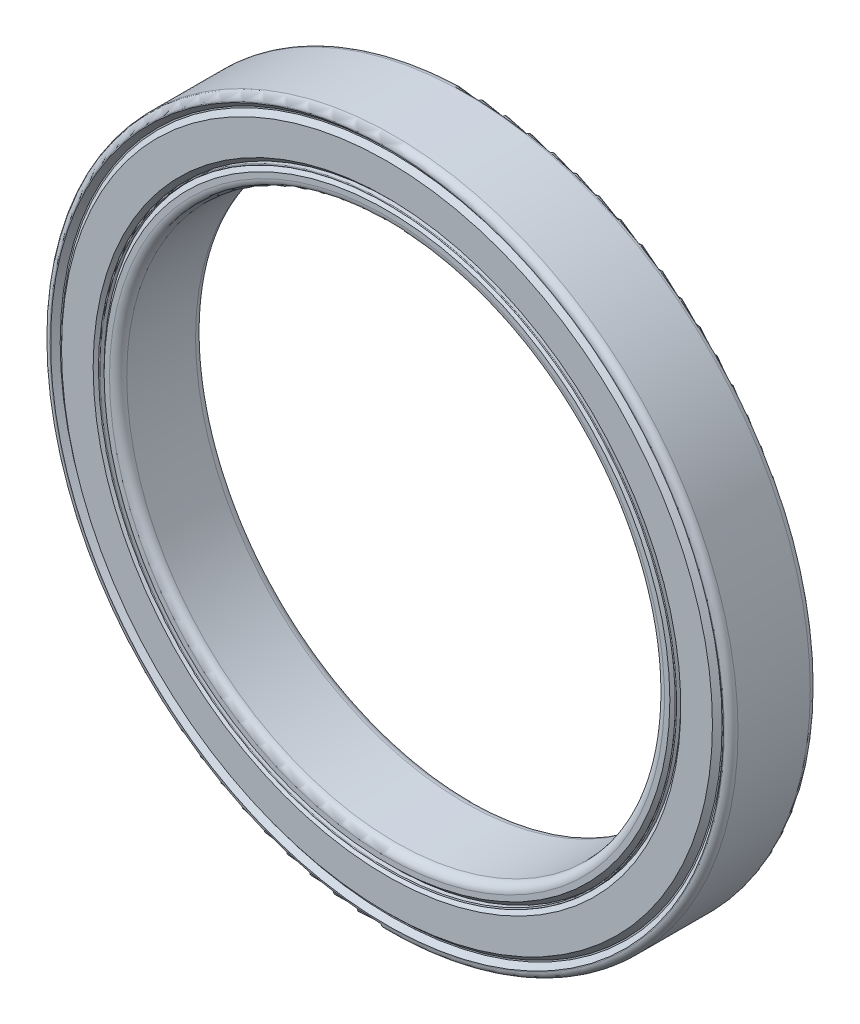
SolidWorks part; units mm, degrees
ref_plane "Front Plane" through (0, 0, 0) normal (0, 0, 1) x (1, 0, 0)
ref_plane "Top Plane" through (0, 0, 0) normal (0, 1, 0) x (1, 0, 0)
ref_plane "Right Plane" through (0, 0, 0) normal (1, 0, 0) x (0, 0, -1)
sketch "Sketch1" plane through (0, 0, 0) normal (0, 0, 1) x (1, 0, 0)
  line L0 (0, 14.25) -> (0, 16) construction
  line L1 (0, 12.5) -> (0, 14.25) construction
  line L2 (0, 16) -> (0, 15.4167) construction
  line L3 (0, 15.4167) -> (0, 14.8333) construction
  line L4 (0, 14.8333) -> (0, 14.25) construction
  circle A0 centre (0, 0) radius 12.5
  circle A1 centre (0, 0) radius 16
  circle A2 centre (0, 0) radius 15.4167 construction
  circle A4 centre (0, 0) radius 13.375 construction
  point P6 (0, 13.375)
  dimension "OD" = 32
  dimension "ID" = 25
sketch "Sketch2" plane through (0, 0, 0) normal (1, 0, 0) x (0, 0, -1)
  line L0 (-2, 16) -> (2, 16) construction
  line L1 (-2, 12.5) -> (-2, -12.5) construction
  line L2 (2, 16) -> (2, -16) construction
  line L3 (2, 0) -> (-2, 0) construction
  dimension "Width" = 4
  dimension "For Shaft Diameter" = 25
  dimension "For Housing ID" = 32
sketch "Sketch3" plane through (0, 0, 0) normal (1, 0, 0) x (0, 0, -1)
  line L0 (-2, -16) -> (2, -16)
  line L1 (2, -16) -> (2, -15.4167)
  line L2 (2, -15.4167) -> (-2, -15.4167)
  line L3 (-2, -15.4167) -> (-2, -16)
  line L4 (-2, 16) -> (2, 16) construction
  line L6 (-2, -12.5) -> (2, -12.5)
  line L9 (-2, -13.375) -> (2, -13.375)
  line L12 (-2, -13.375) -> (-2, -12.5)
  line L13 (2, -13.375) -> (2, -12.5)
  line L14 (-2, 0) -> (2, 0) construction
  point P6 (0, -15.4167)
  point P7 (0, -13.375)
  point P8 (0, -12.5)
  point P20 (0, -16)
  dimension "D1" = 2.0417
revolve "Revolve1" add sketch "Sketch3" angle 360 about L3
sketch "Sketch4" plane through (0, 0, 0) normal (1, 0, 0) x (0, 0, -1)
  line L0 (0, 16) -> (0, -16) construction
  line L1 (-2, -13.375) -> (-2, -15.4167) construction
  circle A0 centre (0, -14.3958) radius 1.225
  point P8 (-2, -14.3958)
  dimension "D1" = 2.45
revolve "Cut-Revolve1" cut sketch "Sketch4" angle 360 about L3
sketch "Sketch5" plane through (0, 0, 0) normal (1, 0, 0) x (0, 0, -1)
  line L0 (0, -13.1708) -> (0, -15.6208)
  line L1 (0, 16) -> (0, -16) construction
  circle A0 centre (0, -14.3958) radius 1.225 construction
  arc A1 (0, -13.1708) -> (0, -15.6208) centre (0, -14.3958) cw
revolve "Revolve2" add sketch "Sketch5" angle 360 about L0
pattern_circular "CirPattern1" count 23 over 360 about axis through (0, 0, 0) along (0, 0, 1) of bodies 138
fillet "Fillet1" radius 0.32 2 edges at (-16, 0, -2) (-16, 0, 2)
fillet "Fillet2" radius 0.4 2 edges at (-12.5, 0, -2) (-12.5, 0, 2)
chamfer "Chamfer1" distance 0.224 angle 45 2 edges at (-15.4167, 0, -2) (-15.4167, 0, 2)
chamfer "Chamfer2" distance 0.224 angle 45 2 edges at (-13.375, 0, -2) (-13.375, 0, 2)
sketch "Sketch6" plane through (0, 0, 0) normal (1, 0, 0) x (0, 0, -1)
  line L0 (-2, -13.6603) -> (-2, -15.1314)
  line L1 (-2, -15.1314) -> (-1.776, -15.3554)
  line L2 (-1.776, -15.3554) -> (-1.776, -15.4167)
  line L3 (-2, -13.6603) -> (-1.776, -13.4363)
  line L4 (-1.776, -13.4363) -> (-1.776, -13.375)
  line L5 (-1.776, 15.4167) -> (-1.776, -15.4167) construction
  line L6 (-1.776, -15.4167) -> (-1.225, -15.4167)
  line L7 (-1.225, -15.4167) -> (-1.225, -13.375)
  line L8 (-1.225, -13.375) -> (-1.776, -13.375)
  line L9 (0, 0) -> (0, 16) construction
  line L10 (1.776, -15.4167) -> (1.225, -15.4167)
  line L11 (1.776, -15.3554) -> (1.776, -15.4167)
  line L12 (2, -15.1314) -> (1.776, -15.3554)
  line L13 (2, -13.6603) -> (2, -15.1314)
  line L14 (2, -13.6603) -> (1.776, -13.4363)
  line L15 (1.776, -13.4363) -> (1.776, -13.375)
  line L16 (1.225, -13.375) -> (1.776, -13.375)
  line L17 (1.225, -15.4167) -> (1.225, -13.375)
  circle A0 centre (0, -14.3958) radius 1.225 construction
  dimension "D1" = 45
  dimension "D2" = 45
  dimension "D3" = 0.0612
revolve "Revolve3" add sketch "Sketch6" angle 360 about L3
sketch "Sketch7" plane through (0, 0, 0) normal (1, 0, 0) x (0, 0, -1)
  line L0 (-1.776, -13.4363) -> (-1.776, -13.375)
  line L1 (-1.776, -13.375) -> (-1.9694, -13.375)
  line L2 (-1.9694, -13.4363) -> (-1.776, -13.4363)
  line L3 (-2, -13.6603) -> (-2, -13.375) construction
  line L4 (0, 16) -> (0, 0) construction
  line L5 (1.776, -13.375) -> (1.9694, -13.375)
  line L6 (1.776, -13.4363) -> (1.776, -13.375)
  line L7 (1.9694, -13.4363) -> (1.776, -13.4363)
  arc A0 (-1.9694, -13.375) -> (-1.9694, -13.4363) centre (-1.9694, -13.4056) ccw
  arc A1 (1.9694, -13.375) -> (1.9694, -13.4363) centre (1.9694, -13.4056) cw
revolve "Revolve4" add sketch "Sketch7" angle 360 about L3
equation "\"D1@Sketch4\"=\"D1@Sketch3\"*1.2"
equation "\"D1@Fillet1\"=\"OD@Sketch1\"*0.01"
equation "\"D1@Fillet2\"=\"D1@Fillet1\"*1.25"
equation "\"D1@Chamfer1\"=\"D1@Fillet1\" * 0.7"
equation "\"D1@Chamfer2\"=\"D1@Chamfer1\""
equation "\"D3@Sketch6\"=\"D1@Sketch3\"*0.03"
equation "\"D1@CirPattern1\"=( pi * \"OD@Sketch1\" )  * .5625 / \"D1@Sketch4\""
